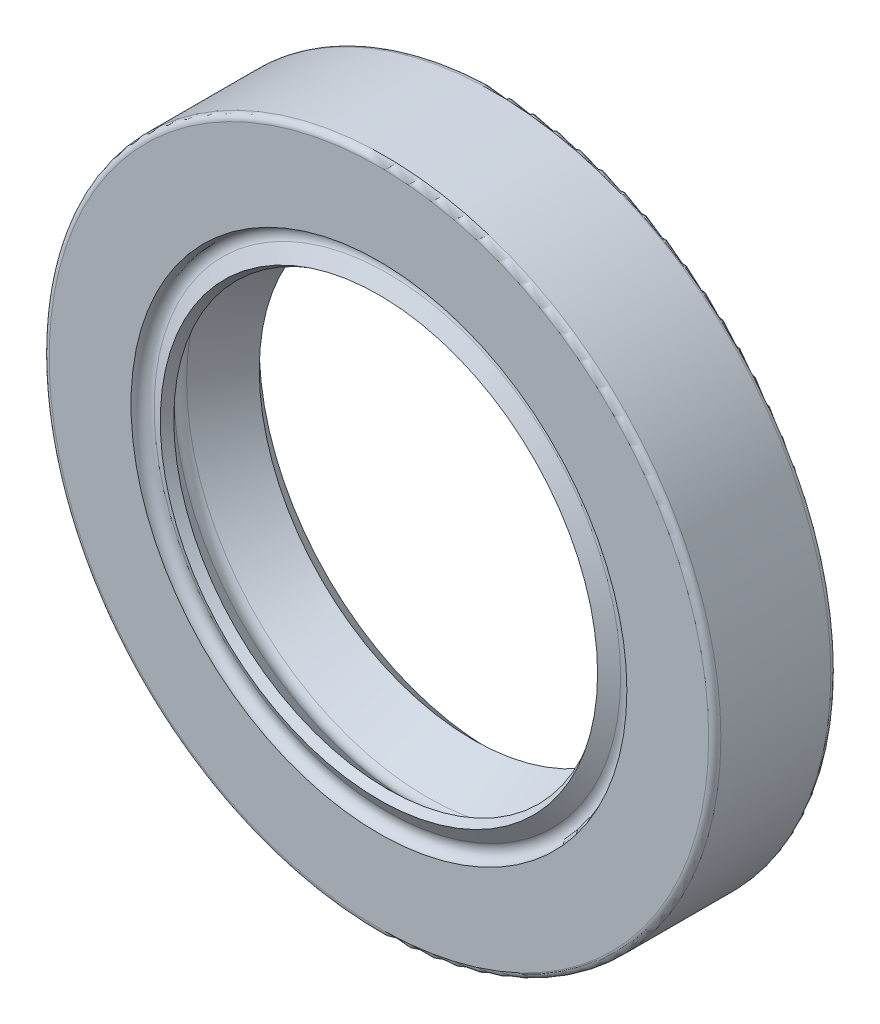
SolidWorks part; units mm, degrees
material "NBR"
ref_plane "Front" through (0, 0, 0) normal (0, 0, 1) x (1, 0, 0)
ref_plane "Top" through (0, 0, 0) normal (0, 1, 0) x (1, 0, 0)
ref_plane "Right" through (0, 0, 0) normal (1, 0, 0) x (0, 0, -1)
sketch "Seal Profile" plane through (0, 0, 0) normal (0, 1, 0) x (1, 0, 0)
  line L0 (275.6667, 1169.5) -> (1378.3333, 1169.5) construction
  line L2 (11, 3.8) -> (11, 0.2)
  line L4 (10.8, 0) -> (8.1203, 0)
  line L5 (10.8, 4) -> (10.2101, 4)
  line L6 (9.5899, 1.1) -> (8.6101, 1.1)
  line L7 (10.0109, 3.8174) -> (9.7891, 1.2826)
  line L8 (8.3091, 2.4455) -> (8.4109, 1.2826)
  line L9 (7, 0.28) -> (7.1617, 0)
  line L10 (7.1617, 0) -> (7.64, 0.2769)
  line L11 (7, 0.28) -> (7.8078, 1.0878)
  line L12 (7, 3.08) -> (7.8714, 1.5707)
  line L13 (7, 3.08) -> (7.64, 3.72)
  line L14 (7.64, 3.72) -> (8.24, 3.72)
  line L15 (7, 3.08) -> (7, 0.28) construction
  arc A5 (8.24, 3.32) -> (8.3091, 2.4455) centre (8.24, 2.88) ccw
  arc A10 (10.8, 0) -> (11, 0.2) centre (10.8, 0.2) ccw
  arc A11 (10.8, 4) -> (11, 3.8) centre (10.8, 3.8) cw
  arc A12 (9.5899, 1.1) -> (9.7891, 1.2826) centre (9.5899, 1.3) ccw
  arc A13 (10.0109, 3.8174) -> (10.2101, 4) centre (10.2101, 3.8) cw
  arc A14 (8.6101, 1.1) -> (8.4109, 1.2826) centre (8.6101, 1.3) cw
  arc A15 (8.1203, 0) -> (7.64, 0.2769) centre (7.8003, 0) ccw
  arc A16 (7.8078, 1.0878) -> (7.8714, 1.5707) centre (7.525, 1.3707) ccw
  arc A17 (8.24, 3.72) -> (8.24, 3.32) centre (8.24, 3.52) cw
  point P7 (9.9, 2.55)
  point P12 (9.4602, 0)
  point P20 (8.36, 1.864)
  dimension "R1" = 0.2
  dimension "R2" = 0.44
  dimension "R3" = 0.4
  dimension "R4" = 0.32
  dimension "A1" = 95
  dimension "A2" = 95
  dimension "A3" = 135
  dimension "A4" = 105
  dimension "B" = 4
  dimension "D3" = 1.1
  dimension "D4" = 1.1
  dimension "D5" = 0.28
  dimension "D8" = 2.8
  dimension "D7" = 0.64
  dimension "D1" = 7
  dimension "D2" = 11
  dimension "D6" = 0.12
  dimension "D9" = 1.36
sketch "Seal Axis" plane through (0, 0, 0) normal (0, 1, 0) x (1, 0, 0)
  line L0 (0, 0) -> (0, 9.5104) construction
revolve "Seal AOP" add sketch "Seal Profile" angle 360 about L0
equation "\"R1@Seal Profile\" = \"B\" * 0.05"
equation "\"R2@Seal Profile\" = \"B\" * 0.11"
equation "\"R3@Seal Profile\" = \"B\" * 0.1"
equation "\"R4@Seal Profile\" = \"B\" * 0.08"
equation "\"D3@Seal Profile\" = \"B\" * 0.275"
equation "\"D4@Seal Profile\" = \"B\" * 0.275"
equation "\"D5@Seal Profile\" = \"B\" * 0.07"
equation "\"D7@Seal Profile\" = \"B\" * 0.16"
equation "\"D8@Seal Profile\" = \"B\" * 0.7"
equation "\"D6@Seal Profile\" = \"B\" * 0.03"
equation "\"D9@Seal Profile\" = \"B\" * 0.34"
